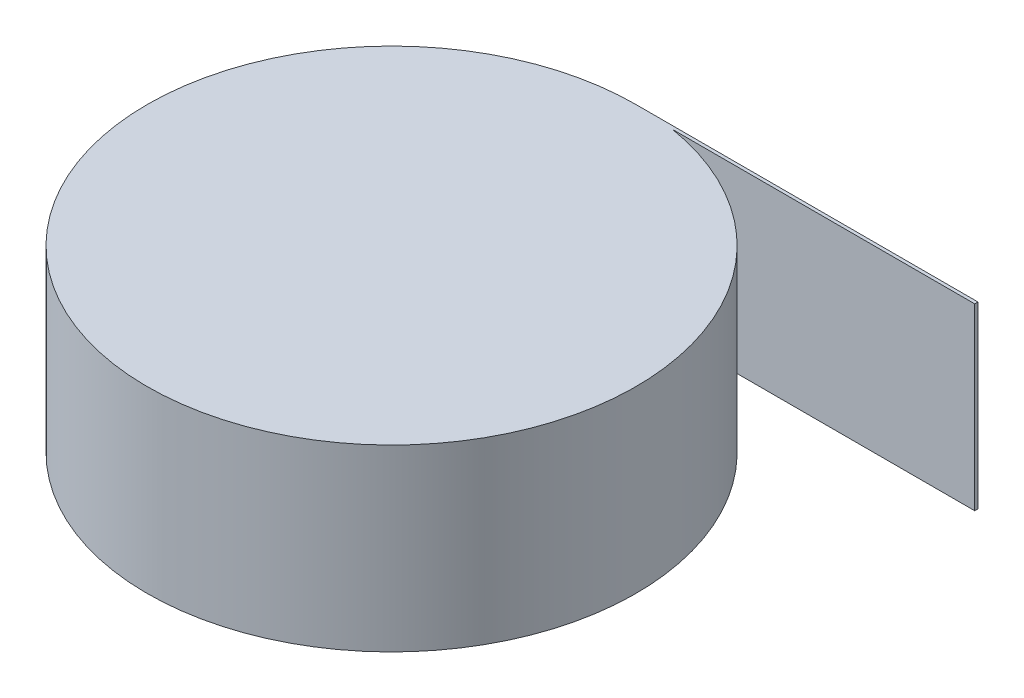
SolidWorks part; units mm, degrees
ref_plane "Front Plane" through (0, 0, 0) normal (0, 0, 1) x (1, 0, 0)
ref_plane "Top Plane" through (0, 0, 0) normal (0, 1, 0) x (1, 0, 0)
ref_plane "Right Plane" through (0, 0, 0) normal (1, 0, 0) x (0, 0, -1)
sketch "Sketch1" plane through (0, 0, 0) normal (0, 1, 0) x (1, 0, 0)
  line L0 (0, 19.05) -> (26.67, 19.05)
  line L1 (26.67, 19.05) -> (26.67, 18.796)
  line L2 (26.67, 18.796) -> (3.1005, 18.796)
  arc A0 (0, 19.05) -> (3.1005, 18.796) centre (0, 0) ccw
  point P1 (26.231, 18.8315)
  dimension "D1" = 38.1
  dimension "D2" = 0.254
  dimension "D3" = 26.67
extrude "Boss-Extrude1" add sketch "Sketch1" along normal blind 13.97
